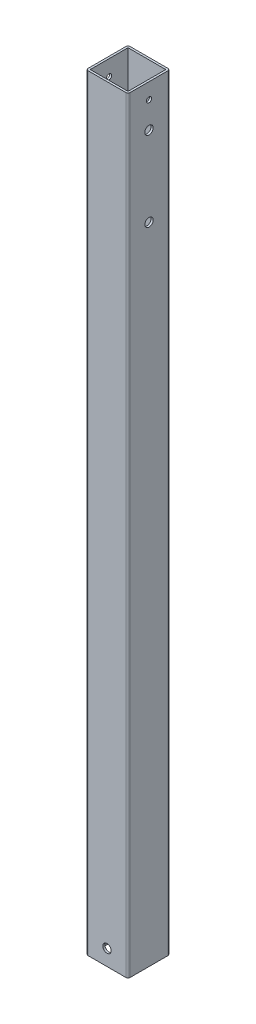
SolidWorks part; units mm, degrees
ref_plane "Front Plane" through (0, 0, 0) normal (0, 0, 1) x (1, 0, 0)
ref_plane "Top Plane" through (0, 0, 0) normal (0, 1, 0) x (1, 0, 0)
ref_plane "Right Plane" through (0, 0, 0) normal (1, 0, 0) x (0, 0, -1)
sketch "Sketch1" plane through (0, 0, 0) normal (0, 1, 0) x (1, 0, 0)
  line L1 (2, 0) -> (38, 0)
  line L2 (0, -2) -> (0, -38)
  line L3 (2, -40) -> (38, -40)
  line L4 (40, -2) -> (40, -38)
  arc A0 (38, 0) -> (40, -2) centre (38, -2) cw
  arc A1 (38, -40) -> (40, -38) centre (38, -38) ccw
  arc A2 (0, -38) -> (2, -40) centre (2, -38) ccw
  arc A3 (2, 0) -> (0, -2) centre (2, -2) ccw
  point P7 (40, 0)
  point P12 (0, -40)
  point P15 (0, 0)
  dimension "D3" = 2
  dimension "D1" = 40
  dimension "D2" = 40
extrude "Extrude-Thin1" add sketch "Sketch1" along normal blind 730 thin
sketch "Sketch2" plane through (0, 0, 40) normal (0, 0, 1) x (1, 0, 0)
  line L0 (38, 15) -> (2, 15) construction
  line L1 (38, 730) -> (38, 0) construction
  line L2 (2, 730) -> (2, 0) construction
  line L3 (2, 0) -> (38, 0) construction
  circle A0 centre (20, 15) radius 4
  dimension "D2" = 8
  dimension "D1" = 15
extrude "Cut-Extrude1" cut sketch "Sketch2" against normal up to surface and the other way through all up to face at (20, 365, 0)
sketch "Sketch5" plane through (0, 0, 0) normal (-1, 0, 0) x (0, 0, 1)
  line L0 (2, 715) -> (38, 715) construction
  line L1 (2, 730) -> (2, 0) construction
  line L2 (38, 730) -> (38, 0) construction
  line L3 (2, 730) -> (38, 730) construction
  circle A0 centre (20, 715) radius 2.5
  dimension "D2" = 5
  dimension "D1" = 15
extrude "Cut-Extrude4" cut sketch "Sketch5" against normal up to surface (40 mm away) contours A0 up to face at (40, 365, 20)
sketch "Sketch6" plane through (40, 0, 0) normal (1, 0, 0) x (0, 0, -1)
  line L0 (-38, 690) -> (-2, 690) construction
  line L1 (-38, 730) -> (-38, 0) construction
  line L2 (-2, 730) -> (-2, 0) construction
  line L3 (-38, 730) -> (-2, 730) construction
  line L4 (-38, 614) -> (-2, 614) construction
  circle A0 centre (-20, 690) radius 4
  circle A2 centre (-20, 614) radius 4
  dimension "D2" = 8
  dimension "D5" = 8
  dimension "D1" = 40
  dimension "D4" = 76
extrude "Cut-Extrude6" cut sketch "Sketch6" against normal up to surface (40 mm away) contours A2 | A0 up to face at (0, 715, 22.5)
